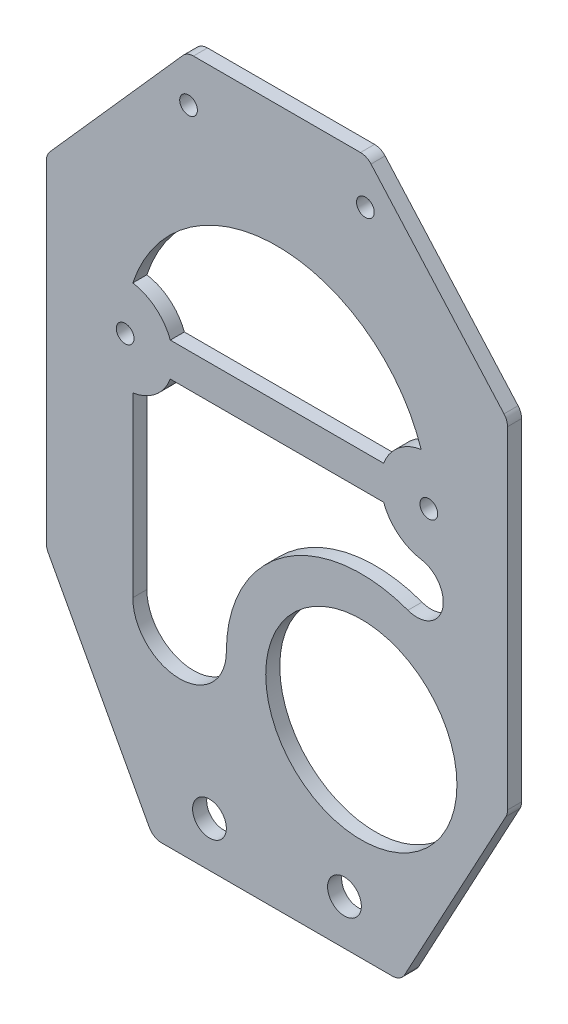
SolidWorks part; units mm, degrees
ref_plane "Front Plane" through (0, 0, 0) normal (0, 0, 1) x (1, 0, 0)
ref_plane "Top Plane" through (0, 0, 0) normal (0, 1, 0) x (1, 0, 0)
ref_plane "Right Plane" through (0, 0, 0) normal (1, 0, 0) x (0, 0, -1)
sketch "Sketch1" plane through (0, 0, 0) normal (0, 0, 1) x (1, 0, 0)
  line L0 (0, 0) -> (0, 248) construction
  line L1 (0, 0) -> (-44, 0)
  line L2 (-44, 0) -> (-82, 70.3989)
  line L3 (-82, 70.3989) -> (-82, 191.5989)
  line L4 (-82, 191.5989) -> (-31.9593, 248)
  line L5 (-31.9593, 248) -> (31.9593, 248)
  line L6 (44, 0) -> (82, 70.3989)
  line L7 (82, 70.3989) -> (82, 191.5989)
  line L8 (82, 191.5989) -> (31.9593, 248)
  line L9 (-54, 150.3989) -> (54, 150.3989) construction
  line L10 (-37.9338, 156.3989) -> (37.9338, 156.3989)
  line L11 (-37.9338, 144.3989) -> (37.9338, 144.3989) construction
  line L12 (-37.9338, 144.3989) -> (-37.9338, 156.3989) construction
  line L13 (-37.9338, 156.3989) -> (37.9338, 156.3989) construction
  line L14 (37.9338, 144.3989) -> (37.9338, 156.3989) construction
  line L15 (-37.9338, 144.3989) -> (37.9338, 156.3989) construction
  line L16 (-37.9338, 156.3989) -> (37.9338, 144.3989) construction
  line L17 (54, 150.3989) -> (46.5632, 115.4506) construction
  line L18 (-51.2766, 133.4665) -> (-51.2766, 70.3989)
  line L19 (-37.9338, 144.3989) -> (37.9338, 144.3989)
  line L20 (0, 0) -> (44, 0)
  circle A0 centre (-31.4496, 232) radius 3.15
  circle A2 centre (-24, 16) radius 3.15
  circle A3 centre (-54, 150.3989) radius 3.15
  circle A4 centre (24, 16) radius 3.15
  circle A5 centre (31.4496, 232) radius 3.15
  circle A6 centre (54, 150.3989) radius 3.15
  circle A7 centre (30, 70.3989) radius 34
  circle A8 centre (54, 150.3989) radius 17.15 construction
  circle A9 centre (-54, 150.3989) radius 17.15 construction
  circle A10 centre (30, 70.3989) radius 48 construction
  arc A11 (-51.2766, 167.3313) -> (51.2766, 167.3313) centre (0, 150.3989) cw
  arc A12 (-51.2766, 167.3313) -> (-37.9338, 156.3989) centre (-54, 150.3989) cw
  arc A13 (37.9338, 156.3989) -> (51.2766, 167.3313) centre (54, 150.3989) cw
  arc A14 (-37.9338, 144.3989) -> (-51.2766, 133.4665) centre (-54, 150.3989) cw
  arc A15 (37.9338, 144.3989) -> (51.2766, 133.4665) centre (54, 150.3989) ccw
  arc A16 (51.2766, 133.4665) -> (46.5632, 115.4506) centre (49.7912, 124.2306) cw
  arc A17 (46.5632, 115.4506) -> (-18, 70.3989) centre (30, 70.3989) ccw
  arc A18 (-51.2766, 70.3989) -> (-18, 70.3989) centre (-34.6383, 70.3989) ccw
  dimension "D2" = 6.3
  dimension "D5" = 44
  dimension "D8" = 28
  dimension "D9" = 6.3
  dimension "D10" = 6.3
  dimension "D16" = 68
  dimension "D19" = 54
  dimension "D1" = 248
  dimension "D3" = 24
  dimension "D4" = 16
  dimension "D6" = 80
  dimension "D7" = 121.2
  dimension "D11" = 41.2
  dimension "D12" = 11
  dimension "D13" = 16
  dimension "D14" = 75.4
  dimension "D15" = 82
  dimension "D17" = 52
  dimension "D20" = 12
  dimension "D18" = 14
extrude "Boss-Extrude2" add sketch "Sketch1" along normal blind 5
fillet "Fillet1" radius 5 8 edges at (82, 70.3989, 2.5) (44, 0, 2.5) (-44, 0, 2.5) (-82, 70.3989, 2.5) (-82, 191.5989, 2.5) (-31.9593, 248, 2.5) (31.9593, 248, 2.5) (82, 191.5989, 2.5)
sketch "Sketch2" plane through (0, 0, 0) normal (0, 0, -1) x (-1, 0, 0)
  circle A0 centre (24, 16) radius 6
  circle A1 centre (-24, 16) radius 6
  dimension "D1" = 12
extrude "Cut-Extrude1" cut sketch "Sketch2" against normal through all
